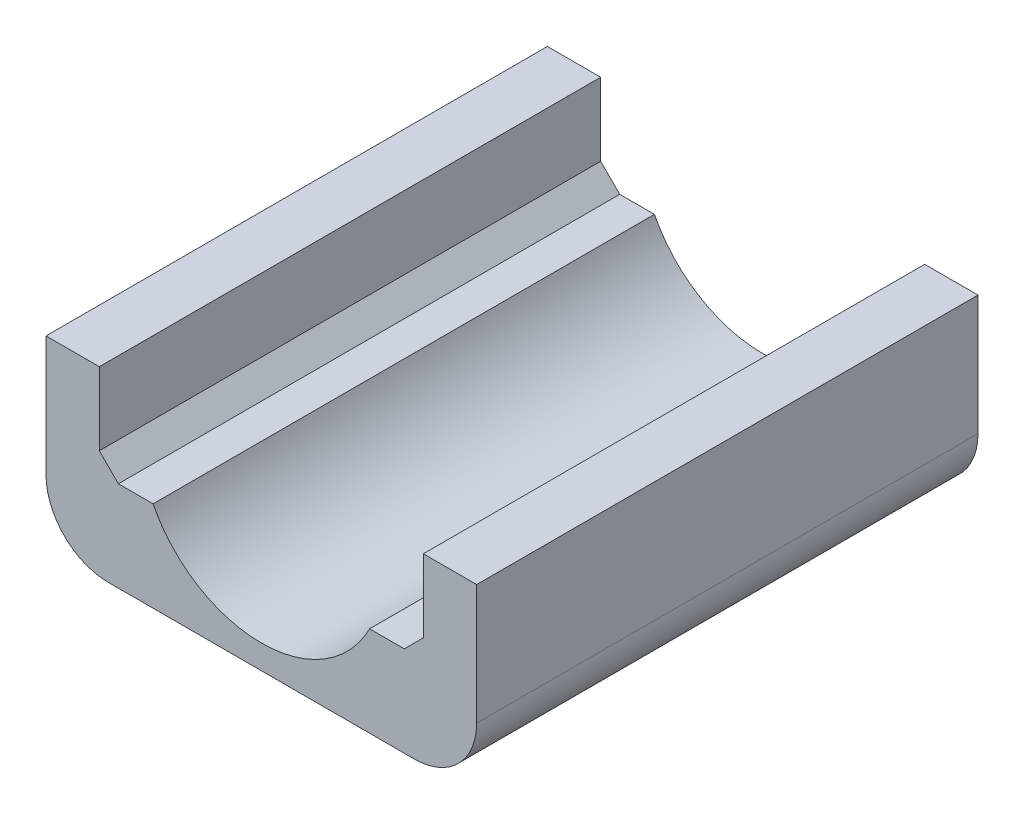
SolidWorks part; units mm, degrees
ref_plane "Front Plane" through (0, 0, 0) normal (0, 0, 1) x (1, 0, 0)
ref_plane "Top Plane" through (0, 0, 0) normal (0, 1, 0) x (1, 0, 0)
ref_plane "Right Plane" through (0, 0, 0) normal (1, 0, 0) x (0, 0, -1)
sketch "Sketch1" plane through (0, 0, 0) normal (0, 0, 1) x (1, 0, 0)
  line L3 (-22.4964, 29.27) -> (-22.4964, 10)
  line L4 (-22.4964, 29.27) -> (-13.9364, 29.27)
  line L9 (-13.9364, 29.27) -> (-13.9364, 17.58)
  line L10 (-13.9364, 17.58) -> (-10.8746, 14.5182)
  line L11 (-10.8746, 14.5182) -> (-5.3046, 14.5182)
  line L12 (-12.4964, 0) -> (36.6487, 0)
  line L14 (46.6487, 29.27) -> (46.6487, 10)
  line L16 (-5.3046, 14.5182) -> (5.4996, 14.5182) construction
  line L17 (46.6487, 29.27) -> (38.0887, 29.27)
  line L18 (38.0887, 29.27) -> (38.0887, 17.58)
  line L19 (38.0887, 17.58) -> (35.027, 14.5182)
  line L20 (35.027, 14.5182) -> (29.457, 14.5182)
  arc A2 (-12.4964, 0) -> (-22.4964, 10) centre (-12.4964, 10) cw
  arc A4 (36.6487, 0) -> (46.6487, 10) centre (36.6487, 10) ccw
  arc A5 (-5.3046, 14.5182) -> (29.457, 14.5182) centre (12.0762, 23.3589) ccw
  point P9 (-22.4964, 0)
  point P12 (35.9136, 0)
  dimension "D3" = 8.56
  dimension "D6" = 10
  dimension "D1" = 58.41
  dimension "D2" = 29.27
  dimension "D8" = 11.69
  dimension "D9" = 11.69
  dimension "D10" = 4.33
  dimension "D11" = 135
  dimension "D12" = 5.57
  dimension "D15" = 19.5
extrude "Boss-Extrude1" add sketch "Sketch1" along normal blind 80.5
